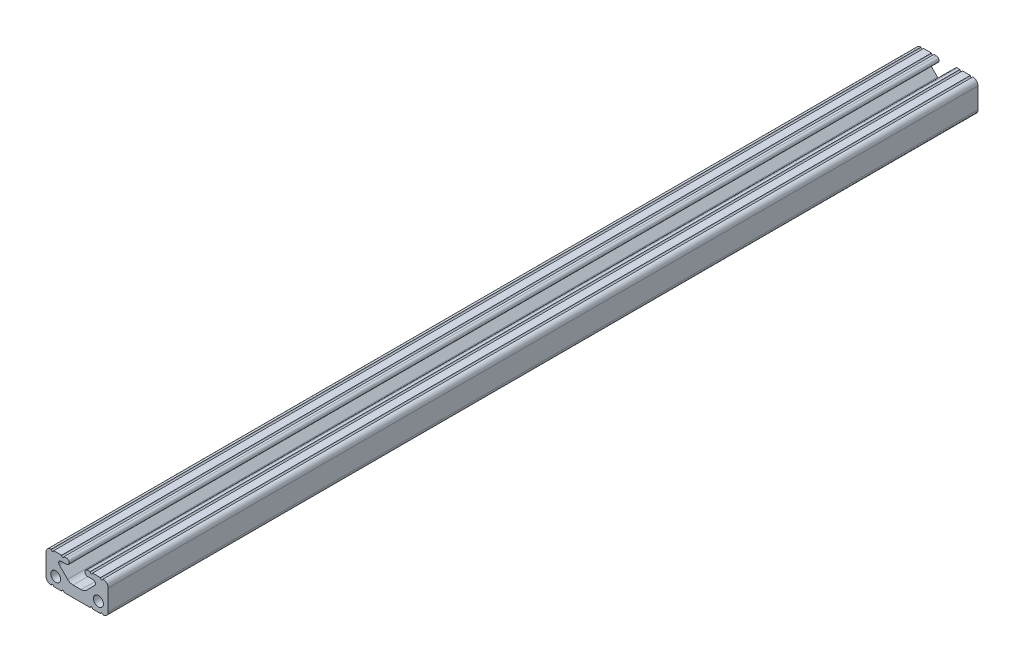
SolidWorks part; units mm, degrees
ref_plane "Front" through (0, 0, 0) normal (0, 0, 1) x (1, 0, 0)
ref_plane "Top" through (0, 0, 0) normal (0, 1, 0) x (1, 0, 0)
ref_plane "Right" through (0, 0, 0) normal (1, 0, 0) x (0, 0, -1)
sketch "Sketch1" plane through (0, 0, 0) normal (0, 0, 1) x (1, 0, 0)
  line L0 (-3.1974, 11.5951) -> (3.1974, 11.5951) construction
  line L1 (-7.504, 9.4742) -> (7.504, 9.4742) construction
  line L28 (-12.7, 10.5918) -> (-12.7, 2.1082)
  line L29 (-9.5504, 0) -> (-6.3246, 0)
  line L30 (-5.3086, 0) -> (5.3086, 0)
  line L31 (6.3246, 0) -> (9.5504, 0)
  line L32 (12.7, 2.1082) -> (12.7, 10.5918)
  line L33 (9.5504, 12.7) -> (6.3246, 12.7)
  line L34 (5.3086, 12.7) -> (4.3023, 12.7)
  line L35 (4.3023, 10.4902) -> (6.488, 10.4902)
  line L36 (7.2064, 8.7558) -> (3.8763, 5.4257)
  line L37 (1.6313, 4.4958) -> (-1.6313, 4.4958)
  line L38 (-3.8763, 5.4257) -> (-7.2064, 8.7558)
  line L39 (-6.488, 10.4902) -> (-4.3023, 10.4902)
  line L40 (-4.3023, 12.7) -> (-5.3086, 12.7)
  line L41 (-6.3246, 12.7) -> (-9.5504, 12.7)
  circle A0 centre (-8.7312, 3.9624) radius 2.032
  circle A1 centre (8.7312, 3.9624) radius 2.032
  arc A36 (-12.7, 2.1082) -> (-10.5791, 0) centre (-10.5918, 2.1082) ccw
  arc A37 (-9.5504, 0) -> (-10.5791, 0) centre (-10.0648, -0.0064) ccw
  arc A38 (-5.3086, 0) -> (-6.3246, 0) centre (-5.8166, 0) ccw
  arc A39 (6.3246, 0) -> (5.3086, 0) centre (5.8166, 0) ccw
  arc A40 (10.5791, 0) -> (9.5504, 0) centre (10.0648, -0.0064) ccw
  arc A41 (10.5791, 0) -> (12.7, 2.1082) centre (10.5918, 2.1082) ccw
  arc A42 (12.7, 10.5918) -> (10.5791, 12.7) centre (10.5918, 10.5918) ccw
  arc A43 (9.5504, 12.7) -> (10.5791, 12.7) centre (10.0648, 12.7063) ccw
  arc A44 (5.3086, 12.7) -> (6.3246, 12.7) centre (5.8166, 12.7) ccw
  arc A45 (4.3023, 12.7) -> (4.3023, 10.4902) centre (4.3023, 11.5951) ccw
  arc A46 (7.2064, 8.7558) -> (6.488, 10.4902) centre (6.488, 9.4742) ccw
  arc A47 (1.6313, 4.4958) -> (3.8763, 5.4257) centre (1.6313, 7.6708) ccw
  arc A48 (-3.8763, 5.4257) -> (-1.6313, 4.4958) centre (-1.6313, 7.6708) ccw
  arc A49 (-6.488, 10.4902) -> (-7.2064, 8.7558) centre (-6.488, 9.4742) ccw
  arc A50 (-4.3023, 10.4902) -> (-4.3023, 12.7) centre (-4.3023, 11.5951) ccw
  arc A51 (-6.3246, 12.7) -> (-5.3086, 12.7) centre (-5.8166, 12.7) ccw
  arc A52 (-10.5791, 12.7) -> (-9.5504, 12.7) centre (-10.0648, 12.7063) ccw
  arc A53 (-10.5791, 12.7) -> (-12.7, 10.5918) centre (-10.5918, 10.5918) ccw
extrude "Boss-Extrude1" add sketch "Sketch1" along normal mid plane 355.6
